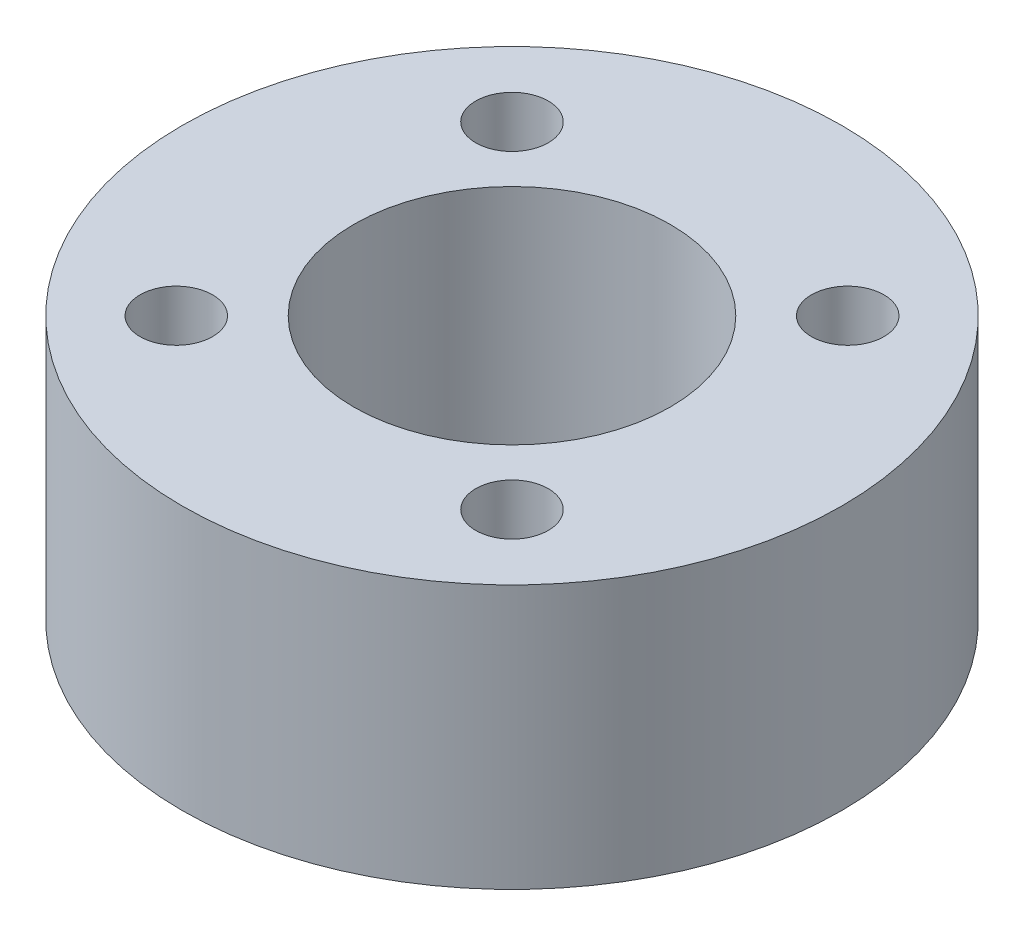
SolidWorks part; units mm, degrees
material "2024-T3"
ref_plane "正面" through (0, 0, 0) normal (0, 0, 1) x (1, 0, 0)
ref_plane "平面" through (0, 0, 0) normal (0, 1, 0) x (1, 0, 0)
ref_plane "右側面" through (0, 0, 0) normal (1, 0, 0) x (0, 0, -1)
sketch "ｽｹｯﾁ1" plane through (0, 0, 0) normal (0, 1, 0) x (1, 0, 0)
  circle A0 centre (0, 0) radius 25
  dimension "D1" = 50
extrude "ﾎﾞｽ - 押し出し1" add sketch "ｽｹｯﾁ1" along normal blind 20
sketch "ｽｹｯﾁ2" plane through (0, 20, 0) normal (0, 1, 0) x (1, 0, 0)
  circle A0 centre (0, 0) radius 12
  dimension "D1" = 24
sketch "ｽｹｯﾁ5" plane through (0, 0, 0) normal (0, -1, 0) x (1, 0, 0)
  line L0 (-12.7279, 12.7279) -> (12.7279, -12.7279)
  line L1 (-12.7279, 12.7279) -> (12.7279, 12.7279)
  line L2 (-12.7279, 12.7279) -> (-12.7279, -12.7279)
  line L3 (-12.7279, -12.7279) -> (12.7279, -12.7279)
  line L4 (12.7279, 12.7279) -> (12.7279, -12.7279)
  line L5 (12.7279, 12.7279) -> (-12.7279, -12.7279)
  circle A0 centre (-12.7279, 12.7279) radius 2.5
  circle A1 centre (-12.7279, -12.7279) radius 2.5
  circle A2 centre (12.7279, -12.7279) radius 2.5
  circle A3 centre (12.7279, 12.7279) radius 2.5
  point P0 (-12.7279, 12.7279)
  point P1 (12.7279, -12.7279)
  point P2 (-12.7279, -12.7279)
  point P3 (12.7279, 12.7279)
  point P4 (0, 0)
  dimension "D2" = 5
  dimension "D3" = 5
  dimension "D4" = 5
  dimension "D5" = 5
  dimension "D1" = 18
extrude "ｶｯﾄ - 押し出し1" cut sketch "ｽｹｯﾁ2" against normal through all contours A0
hole_wizard "M5 すきま穴1" positions "ｽｹｯﾁ5" profile "ｽｹｯﾁ6" hole size "M5" standard "JIS" end condition through all
sketch "ｽｹｯﾁ6" plane through (-12.7279, 0, 12.7279) normal (1, 0, 0) x (0, 0, -1)
  line L0 (0, 0) -> (0, 20)
  line L1 (0, 20) -> (2.75, 20)
  line L2 (2.75, 20) -> (2.75, 0)
  line L5 (2.75, 0) -> (0, 0)
  line L11 (0, -6.35) -> (0, 107.95) construction
  dimension "通し穴の直径" = 5.5
  dimension "通し穴の深さ" = 20
